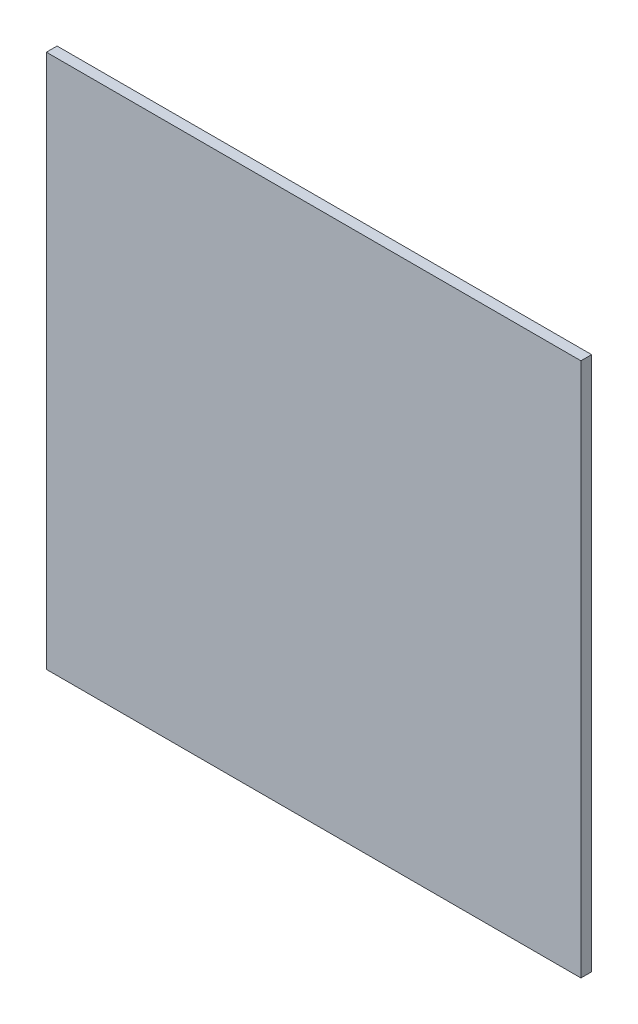
SolidWorks part; units mm, degrees
ref_plane "Alzado" through (0, 0, 0) normal (0, 0, 1) x (1, 0, 0)
ref_plane "Planta" through (0, 0, 0) normal (0, 1, 0) x (1, 0, 0)
ref_plane "Vista lateral" through (0, 0, 0) normal (1, 0, 0) x (0, 0, -1)
sketch "Croquis1" plane through (0, 0, 0) normal (0, 0, 1) x (1, 0, 0)
  line L1 (0, 0) -> (100, 0)
  line L2 (0, 0) -> (0, 100)
  line L3 (0, 100) -> (100, 100)
  line L4 (100, 0) -> (100, 100)
  dimension "D1" = 100
extrude "Saliente-Extruir1" add sketch "Croquis1" along normal blind 2
